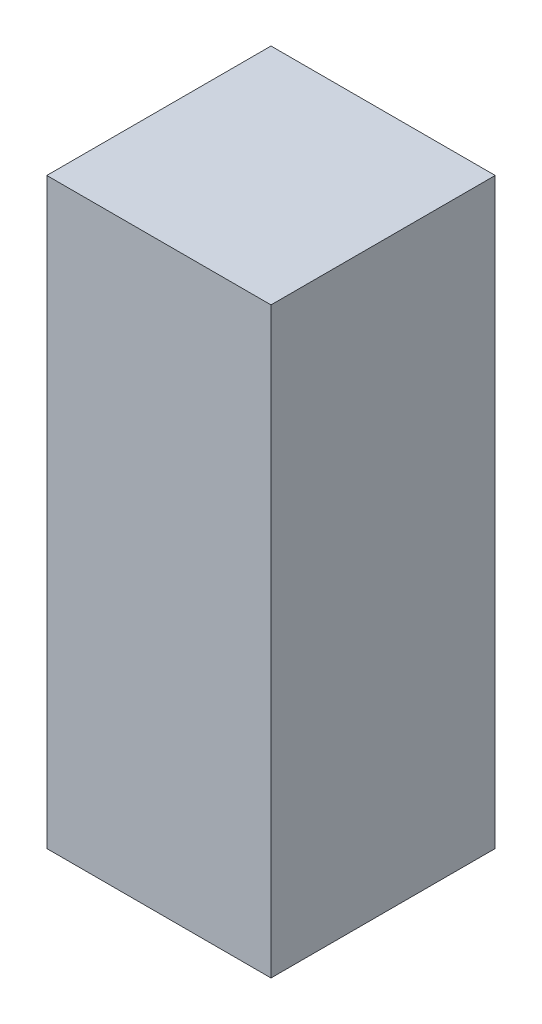
SolidWorks part; units mm, degrees
ref_plane "Front Plane" through (0, 0, 0) normal (0, 0, 1) x (1, 0, 0)
ref_plane "Top Plane" through (0, 0, 0) normal (0, 1, 0) x (1, 0, 0)
ref_plane "Right Plane" through (0, 0, 0) normal (1, 0, 0) x (0, 0, -1)
sketch "SK_P01_MicroFit306posmated" plane through (0, 0, 0) normal (0, 1, 0) x (1, 0, 0)
  line L0 (-5, -5) -> (5, -5)
  line L1 (5, -5) -> (5, 5)
  line L2 (5, 5) -> (-5, 5)
  line L3 (-5, 5) -> (-5, -5)
extrude "P01_MicroFit306posmated" add sketch "SK_P01_MicroFit306posmated" along normal blind 26
